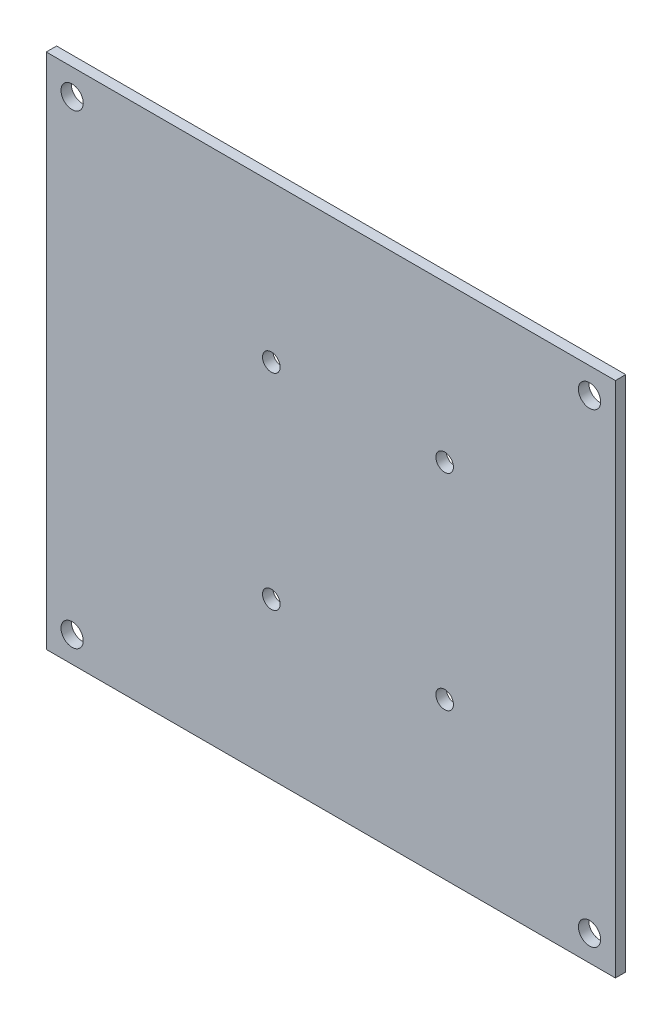
SolidWorks part; units mm, degrees
ref_plane "Спереди" through (0, 0, 0) normal (0, 0, 1) x (1, 0, 0)
ref_plane "Сверху" through (0, 0, 0) normal (0, 1, 0) x (1, 0, 0)
ref_plane "Справа" through (0, 0, 0) normal (1, 0, 0) x (0, 0, -1)
sketch "Эскиз1" plane through (0, 0, 0) normal (0, 0, 1) x (1, 0, 0)
  line L1 (-55, 50) -> (55, 50)
  line L2 (-55, 50) -> (-55, -50)
  line L3 (-55, -50) -> (55, -50)
  line L4 (55, 50) -> (55, -50)
  line L5 (0, -50) -> (0, 50) construction
  line L6 (-55, 0) -> (55, 0) construction
  circle A0 centre (-50, 45) radius 2.15
  circle A1 centre (50, 45) radius 2.15
  circle A2 centre (50, -45) radius 2.15
  circle A3 centre (-50, -45) radius 2.15
  point P0 (0, 0)
  dimension "D3" = 4.3
  dimension "D4" = 5
  dimension "D5" = 5
  dimension "D1" = 110
  dimension "D2" = 100
extrude "Бобышка-Вытянуть1" add sketch "Эскиз1" along normal mid plane 2
sketch "Эскиз2" plane through (0, 0, 1) normal (0, 0, 1) x (1, 0, 0)
  circle A0 centre (22, 19.85) radius 1.7
  circle A1 centre (-11.5, 19.85) radius 1.7
  circle A2 centre (22, -19.8859) radius 1.7
  circle A3 centre (-11.5, -19.85) radius 1.7
  dimension "D1" = 3.4
extrude "Вырез-Вытянуть1" cut sketch "Эскиз2" against normal blind 15
